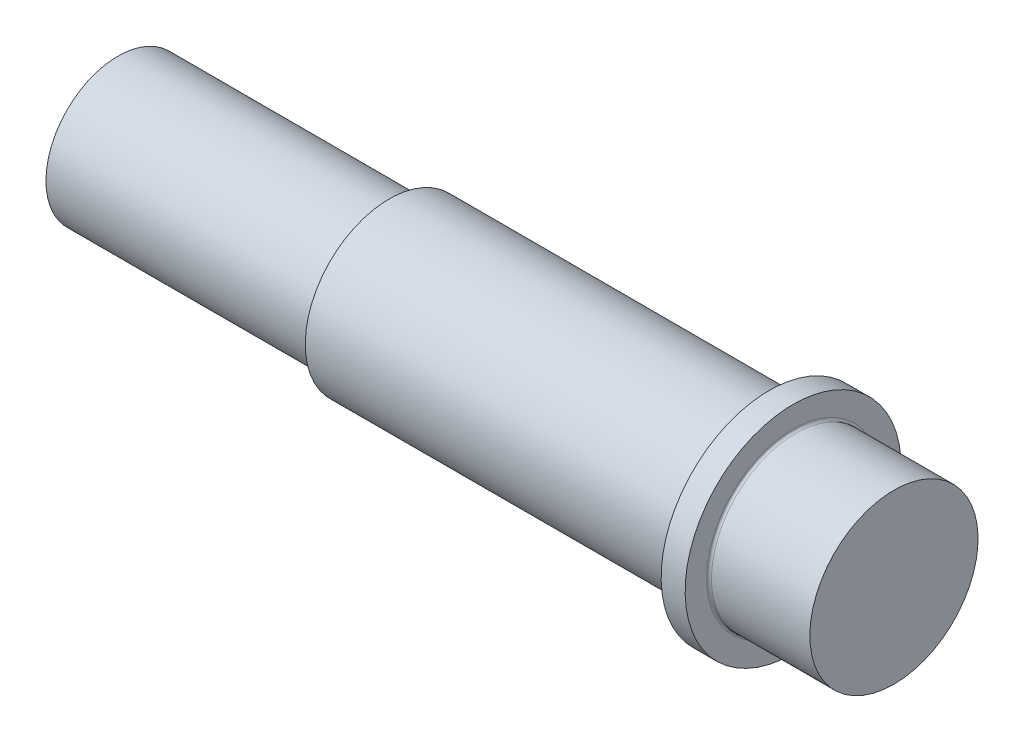
SolidWorks part; units mm, degrees
material "1.0570 (S355J2G3)"
ref_plane "Front Plane" through (0, 0, 0) normal (0, 0, 1) x (1, 0, 0)
ref_plane "Top Plane" through (0, 0, 0) normal (0, 1, 0) x (1, 0, 0)
ref_plane "Right Plane" through (0, 0, 0) normal (1, 0, 0) x (0, 0, -1)
sketch "Sketch1" plane through (0, 0, 0) normal (0, 0, 1) x (1, 0, 0)
  line L0 (-91.4543, 0) -> (91.4543, 0) construction
  line L2 (-80.8167, 15.015) -> (-37.3167, 15.015)
  line L3 (-37.3167, 15.015) -> (-24.3167, 15.015)
  line L5 (27.2805, 17.5) -> (54.8167, 17.5)
  line L6 (54.8167, 17.5) -> (54.8167, 22.5)
  line L7 (54.8167, 22.5) -> (59.8167, 22.5)
  line L8 (59.8167, 22.5) -> (59.8167, 17.5175)
  line L9 (59.8167, 17.5175) -> (80.8167, 17.5175)
  line L11 (-80.8167, 0) -> (80.8167, 0)
  line L12 (-80.8167, 15.015) -> (-80.8167, 0)
  line L13 (80.8167, 17.5175) -> (80.8167, 0)
  line L14 (-24.3167, 15.015) -> (-24.3167, 17.5)
  line L15 (-24.3167, 17.5) -> (27.2805, 17.5)
  point P2 (0, 0)
  point P3 (-30.8167, 15.015)
  point P7 (-30.8167, 15.015)
  point P9 (0, 0)
  dimension "D6" = 45
  dimension "D8" = 35.035
  dimension "D1" = 30.03
  dimension "D2" = 35
  dimension "D3" = 50
  dimension "D4" = 13
  dimension "D5" = 51.5972
  dimension "D7" = 27.5362
  dimension "D9" = 5
  dimension "D10" = 21
revolve "Revolve1" add sketch "Sketch1" angle 360 about L0
fillet "Fillet1" radius 0.5 3 edges at (59.8167, -17.5175, 0) (54.8167, -17.5, 0) (-24.3167, -15.015, 0)
equation "\"alpha\"= 20 'Helix angle, psi [deg]"
equation "\"beta\"= 15 'Pressure angle, theta [deg]"
equation "\"z_1\"= 18 'Number of teeth, pinion 1"
equation "\"z_2\"= 79 'Number of teeth, gear 2"
equation "\"z_3\"= 18 'Number of teeth, pinion 3"
equation "\"z_4\"= 71 'Number of teeth, gear 4"
equation "\"c_dist_1\"= 0.129 'Center distance stage 1 [m]"
equation "\"c_dist_2\"= 0.1788 'Center distance stage 2 [m]"
equation "\"m_s1\"= 2 * \"c_dist_1\" / (\"z_1\" + \"z_2\") * 1000 'Module stage 1 [mm]"
equation "\"m_s2\"= 2 * \"c_dist_2\" / (\"z_3\" + \"z_4\") * 1000 'Module stage 2 [mm]"
equation "\"d_g1\"= \"m_s1\" * \"z_1\" 'Pitch circle 1 [mm]"
equation "\"d_g2\"= \"m_s1\" * \"z_2\" 'Pitch circle 2 [mm]"
equation "\"d_g3\"= \"m_s2\" * \"z_3\" 'Pitch circle 3 [mm]"
equation "\"d_g4\"= \"m_s2\" * \"z_4\" 'Pitch circle 4 [mm]"
equation "\"ht_1\"= \"m_s1\" 'Top height 1 [mm]"
equation "\"ht_2\"= \"m_s1\" 'Top height 2 [mm]"
equation "\"ht_3\"= \"m_s2\" 'Top height 3 [mm]"
equation "\"ht_4\"= \"m_s2\" 'Top height 4 [mm]"
equation "\"hf_1\"= 1.25 * \"m_s1\" 'Bottom height 1 [mm]"
equation "\"hf_2\"= 1.25 * \"m_s1\" 'Bottom height 2 [mm]"
equation "\"hf_3\"= 1.25 * \"m_s2\" 'Bottom height 3 [mm]"
equation "\"hf_4\"= 1.25 * \"m_s2\" 'Bottom height 4 [mm]"
equation "\"dt_g1\"= \"d_g1\" + 2 * \"ht_1\" 'Addendum 1 [mm]"
equation "\"dt_g2\"= \"d_g2\" + 2 * \"ht_2\" 'Addendum 2 [mm]"
equation "\"dt_g3\"= \"d_g3\" + 2 * \"ht_3\" 'Addendum 3 [mm]"
equation "\"dt_g4\"= \"d_g4\" + 2 * \"ht_4\" 'Addendum 4 [mm]"
equation "\"df_g1\"= \"d_g1\" - 2 * \"hf_1\" 'Dedendum 1 [mm]"
equation "\"df_g2\"= \"d_g2\" - 2 * \"hf_2\" 'Dedendum 2 [mm]"
equation "\"df_g3\"= \"d_g3\" - 2 * \"hf_3\" 'Dedendum 3 [mm]"
equation "\"df_g4\"= \"d_g4\" - 2 * \"hf_4\" 'Dedendum 4 [mm]"
equation "\"p_s1\"= pi * \"m_s1\" 'Pitch 1 [mm]"
equation "\"p_s2\"= pi * \"m_s2\" 'Pitch 2 [mm]"
equation "\"sn_s1\"= \"p_s1\" / 2 - 0.05 * \"m_s1\" 'Tooth thickness 1 [mm]"
equation "\"sn_s2\"= \"p_s2\" / 2 - 0.05 * \"m_s2\" 'Tooth thickness 2 [mm]"
equation "\"en_s1\"= \"p_s1\" / 2 + 0.05 * \"m_s1\" 'Hatch width 1 [mm]"
equation "\"en_s2\"= \"p_s2\" / 2 + 0.05 * \"m_s2\" 'Hatch width 2 [mm]"
equation "\"mt_s1\"= \"m_s1\" / cos(\"beta\") 'Helical module 1"
equation "\"mt_s2\"= \"m_s2\" / cos(\"beta\") 'Helical module 2"
equation "\"lambda\"= 10 'Width factor, 8-12"
equation "\"b_s1\"= \"mt_s1\" * \"lambda\" 'Helical gear width 1"
equation "\"b_s2\"= \"mt_s2\" * \"lambda\" 'Helical gear width 2"
equation "\"pt_s1\"= \"p_s1\" / cos(\"beta\") 'Transverse pitch 1 [mm]"
equation "\"pt_s2\"= \"p_s2\" / cos(\"beta\") 'Transverse pitch 2 [mm]"
equation "\"px_s1\"= \"p_s1\" / sin(\"beta\") 'Axial pitch 1 [mm]"
equation "\"px_s2\"= \"p_s2\" / sin(\"beta\") 'Axial pitch 2 [mm]"
equation "\"dp_s1\"= pi / \"pt_s1\" 'Diametral pitch 1 [mm]"
equation "\"dp_s2\"= pi / \"pt_s2\" 'Diametral pitch 2 [mm]"
equation "\"d_S1\"= 35 'Diameter shaft 1 [mm]"
equation "\"d_C\"= 35.035 'Inner diameter bearing C [mm]"
equation "\"d_12\"= 45 'Larger diameter shaft 1 [mm]"
equation "\"d_S2_1\"= 56 'Diameter shaft 2 part 1 [mm]"
equation "\"d_S2_2\"= 56 'Diameter shaft 2 part 2 [mm]"
equation "\"d_D\"= 45.045 'Inner diameter bearing D [mm]"
equation "\"d_E\"= 45.045 'Inner diameter bearing E [mm]"
equation "\"d_45\"= 66 'Larger diameter shaft 2 [mm]"
equation "\"d_S3\"= 66 'Diameter shaft 3 [mm]"
equation "\"d_F\"= 45.045 'Inner diameter bearing F [mm]"
equation "\"d_78\"= 76 'Larger diameter shaft 3 [mm]"
equation "\"b_G1\"= \"b_s1\" 'Gear 1 width [mm]"
equation "\"b_G2\"= \"b_s1\" 'Gear 2 width [mm]"
equation "\"b_G3\"= \"b_s2\" 'Gear 3 width [mm]"
equation "\"b_G4\"= \"b_s2\" 'Gear 4 width [mm]"
equation "\"b_B\"= 13 'Bearing B width [mm]"
equation "\"b_C\"= 21 'Bearing C width [mm]"
equation "\"b_D\"= 25 'Bearing D width [mm]"
equation "\"b_E\"= 25 'Bearing E width [mm]"
equation "\"b_F\"= 19 'Bearing F width [mm]"
equation "\"b_G\"= 18 'Bearing G width [mm]"
equation "\"L_12\"= 5 '[mm]"
equation "\"L_45\"= 5 '[mm]"
equation "\"L_78\"= 5 '[mm]"
equation "\"L_AB\"= 50 '[mm]"
equation "\"L_GH\"= 50 '[mm]"
equation "\"r_S1\"= 0.5 '[mm]"
equation "\"r_S2\"= 1 '[mm]"
equation "\"r_S3\"= 0.6 '[mm] "
equation "\"D1@Fillet1\"= \"r_S1\""
equation "\"d_B\"= 30.03 'Inner diameter bearing B [mm]"
equation "\"d_G\"= 65.065 'Inner diameter bearing G [mm]"
equation "\"D6@Sketch1\"= \"d_12\""
equation "\"D8@Sketch1\"= \"d_C\""
equation "\"D1@Sketch1\"= \"d_B\""
equation "\"D2@Sketch1\"= \"d_S1\""
equation "\"D3@Sketch1\"= \"L_AB\""
equation "\"D4@Sketch1\"= \"b_B\""
equation "\"D5@Sketch1\"= \"L_78\"+\"L_45\"+\"b_s2\""
equation "\"D7@Sketch1\"= \"b_s1\""
equation "\"D9@Sketch1\"= \"L_12\""
equation "\"D10@Sketch1\"= \"b_C\""
